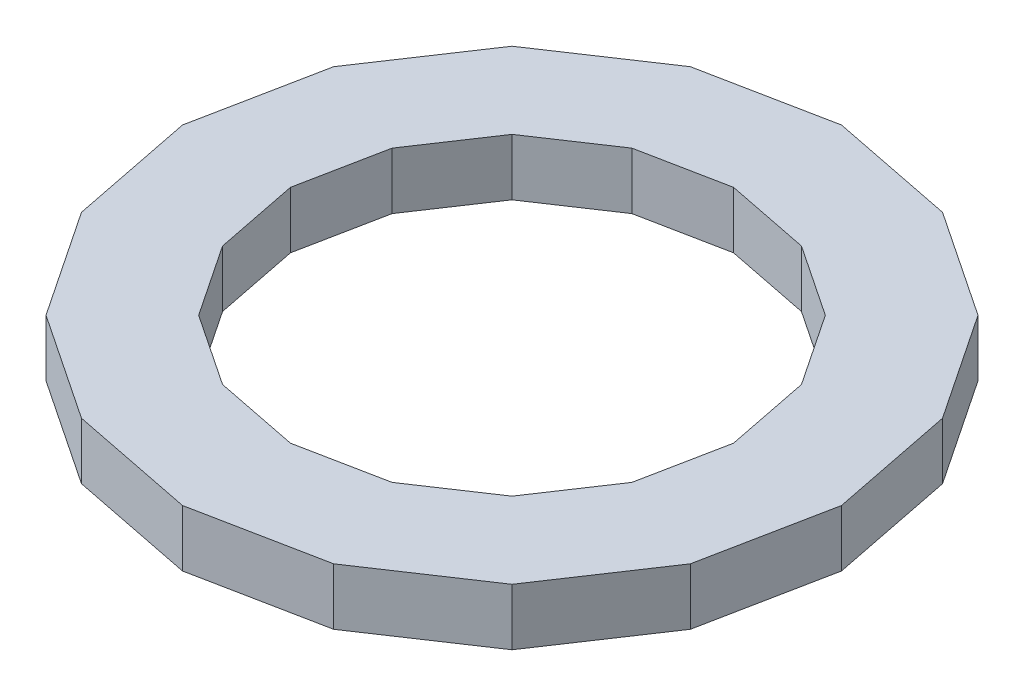
SolidWorks part; units mm, degrees
ref_plane "Front Plane" through (0, 0, 0) normal (0, 0, 1) x (1, 0, 0)
ref_plane "Top Plane" through (0, 0, 0) normal (0, 1, 0) x (1, 0, 0)
ref_plane "Right Plane" through (0, 0, 0) normal (1, 0, 0) x (0, 0, -1)
sketch "Sketch1" plane through (0, 0, 0) normal (0, 1, 0) x (1, 0, 0)
  line L1 (74.41, 0) -> (68.7459, 28.4755)
  line L2 (68.7459, 28.4755) -> (52.6158, 52.6158)
  line L3 (52.6158, 52.6158) -> (28.4755, 68.7459)
  line L4 (28.4755, 68.7459) -> (0, 74.41)
  line L5 (0, 74.41) -> (-28.4755, 68.7459)
  line L6 (-28.4755, 68.7459) -> (-52.6158, 52.6158)
  line L7 (-52.6158, 52.6158) -> (-68.7459, 28.4755)
  line L8 (-68.7459, 28.4755) -> (-74.41, 0)
  line L9 (-74.41, 0) -> (-68.7459, -28.4755)
  line L10 (-68.7459, -28.4755) -> (-52.6158, -52.6158)
  line L11 (-52.6158, -52.6158) -> (-28.4755, -68.7459)
  line L12 (-28.4755, -68.7459) -> (0, -74.41)
  line L13 (0, -74.41) -> (28.4755, -68.7459)
  line L14 (28.4755, -68.7459) -> (52.6158, -52.6158)
  line L15 (52.6158, -52.6158) -> (68.7459, -28.4755)
  line L16 (68.7459, -28.4755) -> (74.41, 0)
  line L17 (110.6667, 0) -> (102.2427, 42.3503)
  line L18 (102.2427, 42.3503) -> (78.2532, 78.2532)
  line L19 (78.2532, 78.2532) -> (42.3503, 102.2427)
  line L20 (42.3503, 102.2427) -> (0, 110.6667)
  line L21 (0, 110.6667) -> (-42.3503, 102.2427)
  line L22 (-42.3503, 102.2427) -> (-78.2532, 78.2532)
  line L23 (-78.2532, 78.2532) -> (-102.2427, 42.3503)
  line L24 (-102.2427, 42.3503) -> (-110.6667, 0)
  line L25 (-110.6667, 0) -> (-102.2427, -42.3503)
  line L26 (-102.2427, -42.3503) -> (-78.2532, -78.2532)
  line L27 (-78.2532, -78.2532) -> (-42.3503, -102.2427)
  line L28 (-42.3503, -102.2427) -> (0, -110.6667)
  line L29 (0, -110.6667) -> (42.3503, -102.2427)
  line L30 (42.3503, -102.2427) -> (78.2532, -78.2532)
  line L31 (78.2532, -78.2532) -> (102.2427, -42.3503)
  line L32 (102.2427, -42.3503) -> (110.6667, 0)
  circle A0 centre (0, 0) radius 72.9803 construction
  circle A1 centre (0, 0) radius 108.5403 construction
  dimension "D1" = 35.56
  dimension "D2" = 43.18
extrude "Boss-Extrude1" add sketch "Sketch1" along normal blind 19.05
